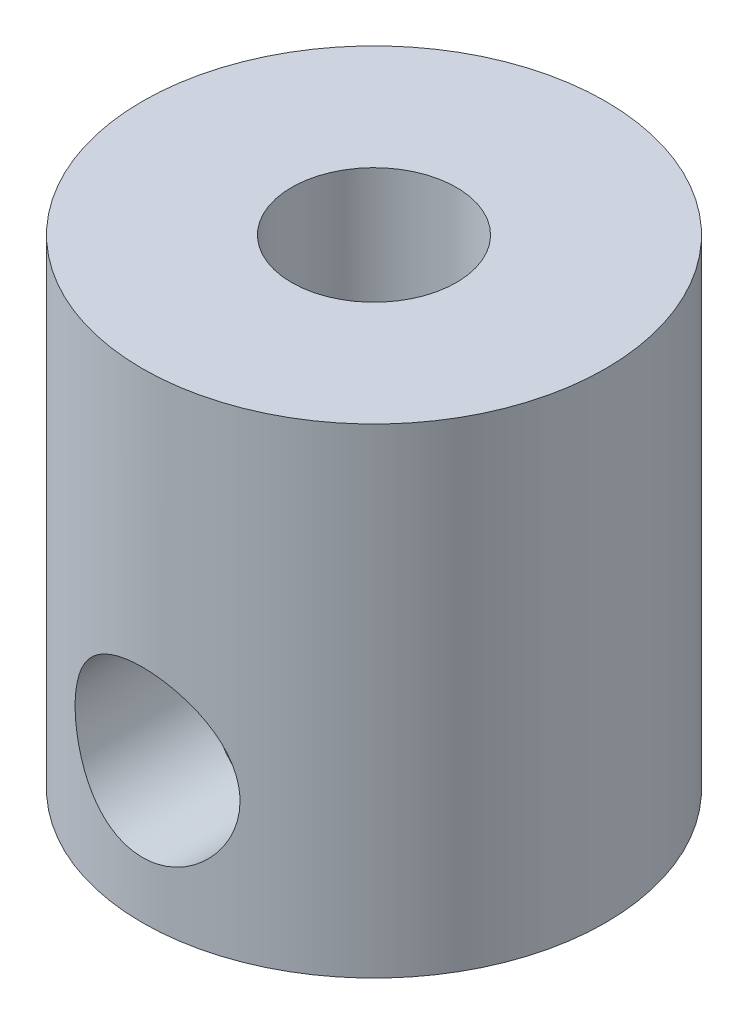
SolidWorks part; units mm, degrees
ref_plane "Front Plane" through (0, 0, 0) normal (0, 0, 1) x (1, 0, 0)
ref_plane "Top Plane" through (0, 0, 0) normal (0, 1, 0) x (1, 0, 0)
ref_plane "Right Plane" through (0, 0, 0) normal (1, 0, 0) x (0, 0, -1)
sketch "Sketch1" plane through (0, 0, 0) normal (0, 1, 0) x (1, 0, 0)
  circle A0 centre (0, 0) radius 3.175
  dimension "D1" = 6.35
extrude "Boss-Extrude1" add sketch "Sketch1" along normal blind 6.5786
sketch "Sketch2" plane through (0, 0, 0) normal (0, -1, 0) x (1, 0, 0)
  circle A0 centre (0, 0) radius 1.5875
  dimension "D1" = 3.175
extrude "Cut-Extrude1" cut sketch "Sketch2" against normal blind 3.81
hole_wizard "#4-40 Tapped Hole1" positions "Sketch5" profile "Sketch4" tap size "#4-40" standard "ANSI Inch"
sketch "Sketch5" plane through (0, 6.5786, 0) normal (0, 1, 0) x (1, 0, 0)
  point P0 (0, 0)
sketch "Sketch4" plane through (0, 6.5786, 0) normal (1, 0, 0) x (0, 0, 1)
  line L0 (0, 0) -> (0, 13.3792)
  line L1 (0, 13.3792) -> (1.1303, 12.7)
  line L2 (1.1303, 12.7) -> (1.1303, 0)
  line L5 (1.1303, 0) -> (0, 0)
  line L10 (0, 13.3792) -> (-1.1303, 12.7) construction
  line L11 (0, -6.35) -> (0, 107.95) construction
  dimension "Tap Drill Dia." = 2.2606
  dimension "Tap Drill Depth" = 12.7
  dimension "Drill Angle" = 118
cosmetic thread "Hole Thread1" parameters "D1"=5.588, "D2"=2.8448
ref_plane "Plane1" through (0, 0, 3.175) normal (0, 0, 1) x (1, 0, 0)
hole_wizard "#4-40 Tapped Hole2" positions "Sketch8" profile "Sketch9" tap size "#4-40" standard "ANSI Inch"
sketch "Sketch8" plane through (0, 0, 3.175) normal (0, 0, 1) x (1, 0, 0)
  line L3 (0, 0) -> (0, 3.81) construction
  point P12 (0, 1.905)
  dimension "D1" = 3.81
sketch "Sketch9" plane through (0, 1.905, 3.175) normal (1, 0, 0) x (0, -1, 0)
  line L0 (0, 0) -> (0, 1.5875)
  line L1 (0, 1.5875) -> (1.1303, 1.5875)
  line L2 (1.1303, 1.5875) -> (1.1303, 0)
  line L5 (1.1303, 0) -> (0, 0)
  line L11 (0, -6.35) -> (0, 107.95) construction
  dimension "Thru Tap Drill Dia." = 2.2606
  dimension "Thru Tap Drill Depth" = 1.5875
cosmetic thread "Hole Thread2" parameters "D2"=2.8448
